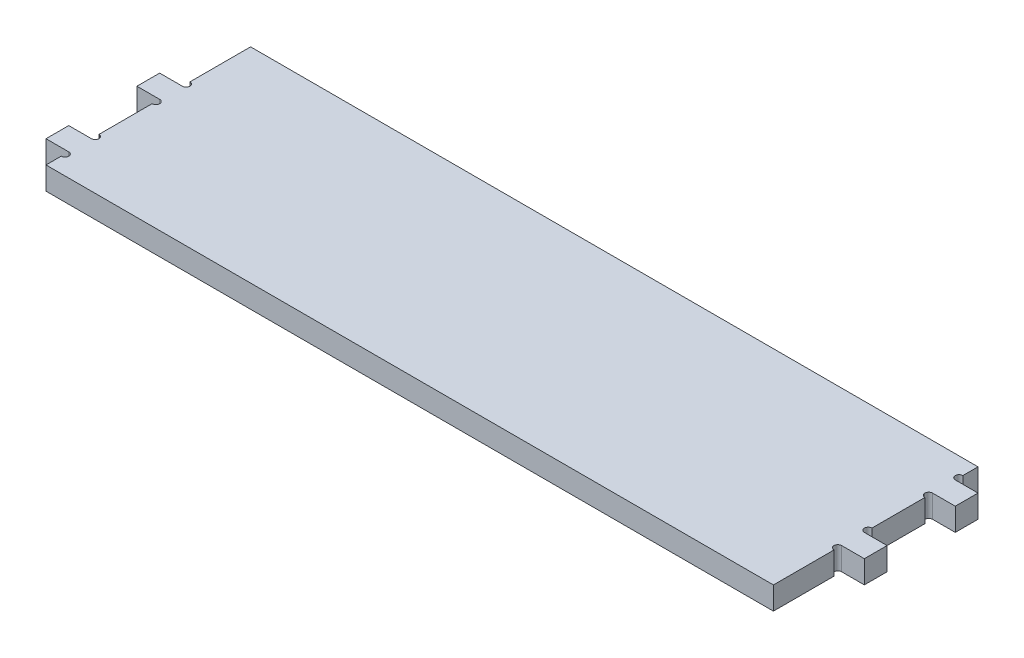
SolidWorks part; units mm, degrees
material "Balsa"
ref_plane "Front Plane" through (0, 0, 0) normal (0, 0, 1) x (1, 0, 0)
ref_plane "Top Plane" through (0, 0, 0) normal (0, 1, 0) x (1, 0, 0)
ref_plane "Right Plane" through (0, 0, 0) normal (1, 0, 0) x (0, 0, -1)
sketch "Sketch1" plane through (0, 0, 0) normal (0, 1, 0) x (1, 0, 0)
  line L0 (-114.3, 171.45) -> (-114.3, 0) construction
  line L1 (0, 0) -> (-304.8, 0)
  line L2 (0, 0) -> (0, 171.45)
  line L3 (0, 171.45) -> (-304.8, 171.45)
  line L4 (-304.8, 0) -> (-304.8, 171.45)
  line L5 (-304.8, 114.3) -> (-323.85, 114.3) construction
  line L6 (-304.8, 114.3) -> (-304.8, 95.25)
  line L7 (-304.8, 95.25) -> (-323.85, 95.25) construction
  line L8 (-323.85, 114.3) -> (-323.85, 95.25) construction
  line L9 (-304.8, 38.1) -> (-323.85, 38.1) construction
  line L10 (-304.8, 38.1) -> (-304.8, 19.05)
  line L11 (-304.8, 19.05) -> (-323.85, 19.05) construction
  line L12 (-323.85, 38.1) -> (-323.85, 19.05) construction
  line L14 (-114.3, 0) -> (-95.25, 0)
  line L15 (-114.3, 0) -> (-114.3, 19.05)
  line L16 (-114.3, 19.05) -> (-95.25, 19.05)
  line L17 (-95.25, 0) -> (-95.25, 19.05)
  line L18 (-114.3, 171.45) -> (-95.25, 171.45)
  line L19 (-114.3, 171.45) -> (-114.3, 152.4)
  line L20 (-114.3, 152.4) -> (-95.25, 152.4)
  line L21 (-95.25, 171.45) -> (-95.25, 152.4)
  dimension "D1" = 171.45
  dimension "D2" = 304.8
  dimension "D3" = 19.05
  dimension "D4" = 190.5
  dimension "D5" = 19.05
  dimension "D6" = 19.05
  dimension "D7" = 114.3
extrude "Boss-Extrude1" add sketch "Sketch1" along normal blind 19.05 contours L0 L19 L3 L4 L1 L15 | L20 L0 L16 L17 L1 L2 L3 L21 | L9 L12 L11 L4 | L5 L8 L7 L4
mirror "Mirror1" about plane through (0, 19.05, 0) normal (-1, 0, 0) of bodies 101
sketch "Sketch2" plane through (0, 19.05, 0) normal (0, 1, 0) x (1, 0, 0)
  line L0 (-304.8, 0) -> (-304.8, 171.45) construction
  line L1 (-304.8, 19.05) -> (-323.85, 19.05)
  line L2 (-304.8, 19.05) -> (-304.8, 38.1)
  line L3 (-304.8, 38.1) -> (-323.85, 38.1)
  line L4 (-323.85, 19.05) -> (-323.85, 38.1)
  line L5 (304.8, 0) -> (304.8, 171.45) construction
  line L6 (-304.8, 95.25) -> (-323.85, 95.25)
  line L7 (-304.8, 95.25) -> (-304.8, 114.3)
  line L8 (-304.8, 114.3) -> (-323.85, 114.3)
  line L9 (-323.85, 95.25) -> (-323.85, 114.3)
  line L10 (304.8, 152.4) -> (323.85, 152.4)
  line L11 (304.8, 152.4) -> (304.8, 133.35)
  line L12 (304.8, 133.35) -> (323.85, 133.35)
  line L13 (323.85, 152.4) -> (323.85, 133.35)
  line L14 (304.8, 0) -> (-304.8, 0) construction
  line L15 (304.8, 76.2) -> (323.85, 76.2)
  line L16 (304.8, 76.2) -> (304.8, 57.15)
  line L17 (304.8, 57.15) -> (323.85, 57.15)
  line L18 (323.85, 76.2) -> (323.85, 57.15)
  dimension "D1" = 19.05
  dimension "D2" = 19.05
  dimension "D3" = 95.25
  dimension "D4" = 57.15
  dimension "D5" = 133.35
extrude "Boss-Extrude2" add sketch "Sketch2" against normal blind 19.05
sketch "Sketch3" plane through (0, 19.05, 0) normal (0, 1, 0) x (1, 0, 0)
  line L0 (304.8, 0) -> (-304.8, 0) construction
  line L1 (-114.3, 0) -> (-95.25, 0)
  line L2 (-114.3, 0) -> (-114.3, 19.05)
  line L3 (-114.3, 19.05) -> (-95.25, 19.05)
  line L4 (-95.25, 0) -> (-95.25, 19.05)
  line L5 (304.8, 171.45) -> (-304.8, 171.45) construction
  line L6 (104.7101, 0) -> (123.7601, 0) construction
  line L7 (104.7101, 0) -> (104.7101, 19.05) construction
  line L8 (104.7101, 19.05) -> (123.7601, 19.05) construction
  line L9 (123.7601, 0) -> (123.7601, 19.05) construction
  line L10 (-95.25, 171.45) -> (-114.3, 171.45)
  line L11 (-95.25, 171.45) -> (-95.25, 152.4)
  line L12 (-95.25, 152.4) -> (-114.3, 152.4)
  line L13 (-114.3, 171.45) -> (-114.3, 152.4)
  dimension "D1" = 19.05
  dimension "D2" = 95.25
extrude "Cut-Extrude1" cut sketch "Sketch3" against normal through all both and the other way through all
mirror "Mirror2" about plane through (0, 0, 0) normal (1, 0, 0) of "Cut-Extrude1"
sketch "Sketch5" plane through (0, 19.05, 0) normal (0, 1, 0) x (1, 0, 0)
  line L0 (0, 0) -> (0, 171.45) construction
  line L1 (95.25, 171.45) -> (-95.25, 171.45) construction
  line L2 (95.25, 0) -> (-95.25, 0) construction
  line L3 (-9.525, 146.05) -> (9.525, 146.05) construction
  line L4 (-9.525, 146.05) -> (-9.525, 127) construction
  line L5 (-9.525, 127) -> (9.525, 127) construction
  line L6 (9.525, 146.05) -> (9.525, 127) construction
  line L7 (-9.525, 146.05) -> (9.525, 127) construction
  line L8 (-9.525, 127) -> (9.525, 146.05) construction
  line L9 (-9.525, 95.25) -> (9.525, 95.25) construction
  line L10 (-9.525, 95.25) -> (-9.525, 76.2) construction
  line L11 (-9.525, 76.2) -> (9.525, 76.2) construction
  line L12 (9.525, 95.25) -> (9.525, 76.2) construction
  line L13 (-9.525, 95.25) -> (9.525, 76.2) construction
  line L14 (-9.525, 76.2) -> (9.525, 95.25) construction
  line L15 (-9.525, 44.45) -> (9.525, 44.45) construction
  line L16 (-9.525, 44.45) -> (-9.525, 25.4) construction
  line L17 (-9.525, 25.4) -> (9.525, 25.4) construction
  line L18 (9.525, 44.45) -> (9.525, 25.4) construction
  line L19 (-9.525, 44.45) -> (9.525, 25.4) construction
  line L20 (-9.525, 25.4) -> (9.525, 44.45) construction
  point P5 (0, 136.525)
  point P10 (0, 85.725)
  point P15 (0, 34.925)
  line B0 (9.525, 131.4901) -> (9.525, 141.5599)
  line B1 (-5.0349, 127) -> (5.0349, 127)
  line B2 (-9.525, 141.5599) -> (-9.525, 131.4901)
  line B3 (5.0349, 146.05) -> (-5.0349, 146.05)
  arc B4 (5.0349, 127) -> (9.525, 131.4901) centre (7.2799, 129.2451) ccw
  arc B5 (-9.525, 131.4901) -> (-5.0349, 127) centre (-7.2799, 129.2451) ccw
  arc B6 (-5.0349, 146.05) -> (-9.525, 141.5599) centre (-7.2799, 143.8049) ccw
  arc B7 (9.525, 141.5599) -> (5.0349, 146.05) centre (7.2799, 143.8049) ccw
  line B8 (9.525, 80.6901) -> (9.525, 90.7599)
  line B9 (-5.0349, 76.2) -> (5.0349, 76.2)
  line B10 (-9.525, 90.7599) -> (-9.525, 80.6901)
  line B11 (5.0349, 95.25) -> (-5.0349, 95.25)
  arc B12 (5.0349, 76.2) -> (9.525, 80.6901) centre (7.2799, 78.4451) ccw
  arc B13 (-9.525, 80.6901) -> (-5.0349, 76.2) centre (-7.2799, 78.4451) ccw
  arc B14 (-5.0349, 95.25) -> (-9.525, 90.7599) centre (-7.2799, 93.0049) ccw
  arc B15 (9.525, 90.7599) -> (5.0349, 95.25) centre (7.2799, 93.0049) ccw
  line B16 (9.525, 29.8901) -> (9.525, 39.9599)
  line B17 (-5.0349, 25.4) -> (5.0349, 25.4)
  line B18 (-9.525, 39.9599) -> (-9.525, 29.8901)
  line B19 (5.0349, 44.45) -> (-5.0349, 44.45)
  arc B20 (5.0349, 25.4) -> (9.525, 29.8901) centre (7.2799, 27.6451) ccw
  arc B21 (-9.525, 29.8901) -> (-5.0349, 25.4) centre (-7.2799, 27.6451) ccw
  arc B22 (-5.0349, 44.45) -> (-9.525, 39.9599) centre (-7.2799, 42.2049) ccw
  arc B23 (9.525, 39.9599) -> (5.0349, 44.45) centre (7.2799, 42.2049) ccw
  dimension "D1" = 19.05
  dimension "D2" = 25.4
  dimension "D3" = 25.4
  dimension "D4" = 31.75
sketch_block_instance "NotchCutoutProfile-1"
sketch_block "NotchCutoutProfile"
sketch_block_instance "NotchCutoutProfile-2"
sketch_block_instance "NotchCutoutProfile-3"
extrude "Cut-Extrude2" cut sketch "Sketch5" against normal through all both
sketch "Sketch6" plane through (0, 19.05, 0) normal (0, 1, 0) x (1, 0, 0)
  line L0 (0, 171.45) -> (0, 0) construction
  line L1 (-114.3, 152.4) -> (-95.25, 152.4) construction
  line L2 (-114.3, 152.4) -> (-114.3, 171.45) construction
  line L3 (-114.3, 171.45) -> (-95.25, 171.45) construction
  line L4 (-95.25, 152.4) -> (-95.25, 171.45) construction
  line L9 (-114.3, 0) -> (-95.25, 0) construction
  line L10 (-114.3, 0) -> (-114.3, 19.05) construction
  line L11 (-114.3, 19.05) -> (-95.25, 19.05) construction
  line L12 (-95.25, 0) -> (-95.25, 19.05) construction
  line L17 (95.25, 171.45) -> (-95.25, 171.45) construction
  line L18 (95.25, 0) -> (95.25, 19.05) construction
  line L19 (114.3, 19.05) -> (95.25, 19.05) construction
  line L20 (114.3, 0) -> (114.3, 19.05) construction
  line L21 (114.3, 0) -> (95.25, 0) construction
  line L22 (95.25, 152.4) -> (95.25, 171.45) construction
  line L23 (114.3, 171.45) -> (95.25, 171.45) construction
  line L24 (114.3, 152.4) -> (114.3, 171.45) construction
  line L25 (114.3, 152.4) -> (95.25, 152.4) construction
  line L26 (-114.3, 171.45) -> (-114.3, 166.9599)
  line L27 (-114.3, 166.9599) -> (-95.25, 166.9599)
  line L28 (-114.3, 4.4901) -> (-95.25, 4.4901)
  line L29 (95.25, 4.4901) -> (114.3, 4.4901)
  line L30 (95.25, 166.9599) -> (114.3, 166.9599)
  line B0 (-95.25, 156.8901) -> (-95.25, 166.9599)
  line B1 (-109.8099, 152.4) -> (-99.7401, 152.4)
  line B2 (-114.3, 166.9599) -> (-114.3, 156.8901)
  line B3 (-99.7401, 171.45) -> (-109.8099, 171.45)
  arc B4 (-99.7401, 152.4) -> (-95.25, 156.8901) centre (-97.4951, 154.6451) ccw
  arc B5 (-114.3, 156.8901) -> (-109.8099, 152.4) centre (-112.0549, 154.6451) ccw
  arc B6 (-109.8099, 171.45) -> (-114.3, 166.9599) centre (-112.0549, 169.2049) ccw
  arc B7 (-95.25, 166.9599) -> (-99.7401, 171.45) centre (-97.4951, 169.2049) ccw
  line B8 (-95.25, 4.4901) -> (-95.25, 14.5599)
  line B9 (-109.8099, 0) -> (-99.7401, 0)
  line B10 (-114.3, 14.5599) -> (-114.3, 4.4901)
  line B11 (-99.7401, 19.05) -> (-109.8099, 19.05)
  arc B12 (-99.7401, 0) -> (-95.25, 4.4901) centre (-97.4951, 2.2451) ccw
  arc B13 (-114.3, 4.4901) -> (-109.8099, 0) centre (-112.0549, 2.2451) ccw
  arc B14 (-109.8099, 19.05) -> (-114.3, 14.5599) centre (-112.0549, 16.8049) ccw
  arc B15 (-95.25, 14.5599) -> (-99.7401, 19.05) centre (-97.4951, 16.8049) ccw
  line B16 (95.25, 156.8901) -> (95.25, 166.9599)
  line B17 (109.8099, 152.4) -> (99.7401, 152.4)
  line B18 (114.3, 166.9599) -> (114.3, 156.8901)
  line B19 (99.7401, 171.45) -> (109.8099, 171.45)
  arc B20 (99.7401, 152.4) -> (95.25, 156.8901) centre (97.4951, 154.6451) cw
  arc B21 (114.3, 156.8901) -> (109.8099, 152.4) centre (112.0549, 154.6451) cw
  arc B22 (109.8099, 171.45) -> (114.3, 166.9599) centre (112.0549, 169.2049) cw
  arc B23 (95.25, 166.9599) -> (99.7401, 171.45) centre (97.4951, 169.2049) cw
  line B24 (95.25, 4.4901) -> (95.25, 14.5599)
  line B25 (109.8099, 0) -> (99.7401, 0)
  line B26 (114.3, 14.5599) -> (114.3, 4.4901)
  line B27 (99.7401, 19.05) -> (109.8099, 19.05)
  arc B28 (99.7401, 0) -> (95.25, 4.4901) centre (97.4951, 2.2451) cw
  arc B29 (114.3, 4.4901) -> (109.8099, 0) centre (112.0549, 2.2451) cw
  arc B30 (109.8099, 19.05) -> (114.3, 14.5599) centre (112.0549, 16.8049) cw
  arc B31 (95.25, 14.5599) -> (99.7401, 19.05) centre (97.4951, 16.8049) cw
sketch_block_instance "NotchCutoutProfile-8"
sketch_block_instance "NotchCutoutProfile-10"
sketch_block_instance "NotchCutoutProfile-12"
sketch_block_instance "NotchCutoutProfile-13"
extrude "Cut-Extrude3" cut sketch "Sketch6" against normal through all both contours B2 B5 B1 B4 B0 L27 | B21 B18 L30 B16 B20 B17 | B31 B24 L29 B26 B30 B27 | B8 B15 B11 B14 B10 L28
sketch "Sketch8" plane through (0, 19.05, 0) normal (0, 1, 0) x (1, 0, 0)
  line L36 (-109.8099, 19.05) -> (-99.7401, 19.05)
  line L37 (-95.25, 14.5599) -> (-95.25, 0)
  line L38 (-95.25, 0) -> (95.25, 0)
  line L39 (95.25, 0) -> (95.25, 14.5599)
  line L40 (99.7401, 19.05) -> (109.8099, 19.05)
  line L41 (114.3, 14.5599) -> (114.3, 0)
  line L42 (114.3, 0) -> (304.8, 0)
  line L43 (304.8, 0) -> (304.8, 57.15)
  line L44 (304.8, 57.15) -> (323.85, 57.15)
  line L45 (323.85, 57.15) -> (323.85, 76.2)
  line L46 (323.85, 76.2) -> (304.8, 76.2)
  line L47 (304.8, 76.2) -> (304.8, 133.35)
  line L48 (304.8, 133.35) -> (323.85, 133.35)
  line L49 (323.85, 133.35) -> (323.85, 152.4)
  line L50 (323.85, 152.4) -> (304.8, 152.4)
  line L51 (304.8, 152.4) -> (304.8, 171.45)
  line L52 (304.8, 171.45) -> (114.3, 171.45)
  line L53 (114.3, 171.45) -> (114.3, 156.8901)
  line L54 (109.8099, 152.4) -> (99.7401, 152.4)
  line L55 (95.25, 156.8901) -> (95.25, 171.45)
  line L56 (95.25, 171.45) -> (-95.25, 171.45)
  line L57 (-95.25, 171.45) -> (-95.25, 156.8901)
  line L58 (-99.7401, 152.4) -> (-109.8099, 152.4)
  line L59 (-114.3, 156.8901) -> (-114.3, 171.45)
  line L60 (-114.3, 171.45) -> (-304.8, 171.45)
  line L61 (-304.8, 171.45) -> (-304.8, 114.3)
  line L62 (-304.8, 114.3) -> (-323.85, 114.3)
  line L63 (-323.85, 114.3) -> (-323.85, 95.25)
  line L64 (-323.85, 95.25) -> (-304.8, 95.25)
  line L65 (-304.8, 95.25) -> (-304.8, 38.1)
  line L66 (-304.8, 38.1) -> (-323.85, 38.1)
  line L67 (-323.85, 38.1) -> (-323.85, 19.05)
  line L68 (-323.85, 19.05) -> (-304.8, 19.05)
  line L69 (-304.8, 19.05) -> (-304.8, 0)
  line L70 (-304.8, 0) -> (-114.3, 0)
  line L71 (-114.3, 0) -> (-114.3, 14.5599)
  line L72 (-109.8099, 19.05) -> (-99.7401, 19.05)
  line L73 (-95.25, 14.5599) -> (-95.25, 0)
  line L74 (-95.25, 0) -> (95.25, 0)
  line L75 (95.25, 0) -> (95.25, 14.5599)
  line L76 (99.7401, 19.05) -> (109.8099, 19.05)
  line L77 (114.3, 14.5599) -> (114.3, 0)
  line L78 (114.3, 0) -> (304.8, 0)
  line L79 (304.8, 0) -> (304.8, 57.15)
  line L80 (304.8, 57.15) -> (323.85, 57.15)
  line L81 (323.85, 57.15) -> (323.85, 76.2)
  line L82 (323.85, 76.2) -> (304.8, 76.2)
  line L83 (304.8, 76.2) -> (304.8, 133.35)
  line L84 (304.8, 133.35) -> (323.85, 133.35)
  line L85 (323.85, 133.35) -> (323.85, 152.4)
  line L86 (323.85, 152.4) -> (304.8, 152.4)
  line L87 (304.8, 152.4) -> (304.8, 171.45)
  line L88 (304.8, 171.45) -> (114.3, 171.45)
  line L89 (114.3, 171.45) -> (114.3, 156.8901)
  line L90 (109.8099, 152.4) -> (99.7401, 152.4)
  line L91 (95.25, 156.8901) -> (95.25, 171.45)
  line L92 (95.25, 171.45) -> (-95.25, 171.45)
  line L93 (-95.25, 171.45) -> (-95.25, 156.8901)
  line L94 (-99.7401, 152.4) -> (-109.8099, 152.4)
  line L95 (-114.3, 156.8901) -> (-114.3, 171.45)
  line L96 (-114.3, 171.45) -> (-304.8, 171.45)
  line L97 (-304.8, 171.45) -> (-304.8, 114.3)
  line L98 (-304.8, 114.3) -> (-323.85, 114.3)
  line L99 (-323.85, 114.3) -> (-323.85, 95.25)
  line L100 (-323.85, 95.25) -> (-304.8, 95.25)
  line L101 (-304.8, 95.25) -> (-304.8, 38.1)
  line L102 (-304.8, 38.1) -> (-323.85, 38.1)
  line L103 (-323.85, 38.1) -> (-323.85, 19.05)
  line L104 (-323.85, 19.05) -> (-304.8, 19.05)
  line L105 (-304.8, 19.05) -> (-304.8, 0)
  line L106 (-304.8, 0) -> (-114.3, 0)
  line L107 (-114.3, 0) -> (-114.3, 14.5599)
  arc A8 (-109.8099, 19.05) -> (-114.3, 14.5599) centre (-112.0549, 16.8049) ccw
  arc A9 (-95.25, 14.5599) -> (-99.7401, 19.05) centre (-97.4951, 16.8049) ccw
  arc A10 (99.7401, 19.05) -> (95.25, 14.5599) centre (97.4951, 16.8049) ccw
  arc A11 (114.3, 14.5599) -> (109.8099, 19.05) centre (112.0549, 16.8049) ccw
  arc A12 (109.8099, 152.4) -> (114.3, 156.8901) centre (112.0549, 154.6451) ccw
  arc A13 (95.25, 156.8901) -> (99.7401, 152.4) centre (97.4951, 154.6451) ccw
  arc A14 (-99.7401, 152.4) -> (-95.25, 156.8901) centre (-97.4951, 154.6451) ccw
  arc A15 (-114.3, 156.8901) -> (-109.8099, 152.4) centre (-112.0549, 154.6451) ccw
  arc A16 (-109.8099, 19.05) -> (-114.3, 14.5599) centre (-112.0549, 16.8049) ccw
  arc A17 (-95.25, 14.5599) -> (-99.7401, 19.05) centre (-97.4951, 16.8049) ccw
  arc A18 (99.7401, 19.05) -> (95.25, 14.5599) centre (97.4951, 16.8049) ccw
  arc A19 (114.3, 14.5599) -> (109.8099, 19.05) centre (112.0549, 16.8049) ccw
  arc A20 (109.8099, 152.4) -> (114.3, 156.8901) centre (112.0549, 154.6451) ccw
  arc A21 (95.25, 156.8901) -> (99.7401, 152.4) centre (97.4951, 154.6451) ccw
  arc A22 (-99.7401, 152.4) -> (-95.25, 156.8901) centre (-97.4951, 154.6451) ccw
  arc A23 (-114.3, 156.8901) -> (-109.8099, 152.4) centre (-112.0549, 154.6451) ccw
  line B0 (-304.8, 95.25) -> (-323.85, 95.25)
  line B1 (-323.85, 95.25) -> (-323.85, 114.3)
  line B2 (-323.85, 114.3) -> (-304.8, 114.3)
  arc B3 (-304.8, 95.25) -> (-304.8, 88.9) centre (-304.8, 92.075) cw
  arc B4 (-304.8, 114.3) -> (-304.8, 120.65) centre (-304.8, 117.475) ccw
  line B5 (-304.8, 19.05) -> (-323.85, 19.05)
  line B6 (-323.85, 19.05) -> (-323.85, 38.1)
  line B7 (-323.85, 38.1) -> (-304.8, 38.1)
  arc B8 (-304.8, 19.05) -> (-304.8, 12.7) centre (-304.8, 15.875) cw
  arc B9 (-304.8, 38.1) -> (-304.8, 44.45) centre (-304.8, 41.275) ccw
  line B10 (304.8, 152.4) -> (323.85, 152.4)
  line B11 (323.85, 152.4) -> (323.85, 133.35)
  line B12 (323.85, 133.35) -> (304.8, 133.35)
  arc B13 (304.8, 152.4) -> (304.8, 158.75) centre (304.8, 155.575) cw
  arc B14 (304.8, 133.35) -> (304.8, 127) centre (304.8, 130.175) ccw
  line B15 (304.8, 76.2) -> (323.85, 76.2)
  line B16 (323.85, 76.2) -> (323.85, 57.15)
  line B17 (323.85, 57.15) -> (304.8, 57.15)
  arc B18 (304.8, 76.2) -> (304.8, 82.55) centre (304.8, 79.375) cw
  arc B19 (304.8, 57.15) -> (304.8, 50.8) centre (304.8, 53.975) ccw
  dimension "D1" = 0
sketch_block_instance "DogBoneCornerNotch-1"
sketch_block "DogBoneCornerNotch" parameters "D1"=19.05, "D2"=19.05, "D3"=19.05
sketch_block_instance "DogBoneCornerNotch-2"
sketch_block_instance "DogBoneCornerNotch-3"
sketch_block_instance "DogBoneCornerNotch-4"
extrude "Cut-Extrude4" cut sketch "Sketch8" against normal through all contours L97 B4 | B3 L101 | L101 B9 | B8 L105 | B13 L87 | L83 B14 | L79 B19 | B18 L83
sketch "Sketch9" plane through (0, 19.05, 0) normal (0, 1, 0) x (1, 0, 0)
  line L0 (-114.3, 171.45) -> (-304.8, 171.45) construction
  line L1 (-120.65, 171.45) -> (120.65, 171.45)
  line L2 (-120.65, 171.45) -> (-120.65, 0)
  line L3 (-120.65, 0) -> (120.65, 0)
  line L4 (120.65, 171.45) -> (120.65, 0)
  line L5 (304.8, 0) -> (114.3, 0) construction
  line L6 (114.3, 171.45) -> (114.3, 156.8901) construction
  line L7 (-114.3, 171.45) -> (-114.3, 156.8901) construction
  dimension "D1" = 6.35
  dimension "D2" = 6.35
extrude "Boss-Extrude3" add sketch "Sketch9" against normal up to surface (19.05 mm away) up to face at (0, 0, -136.525)
